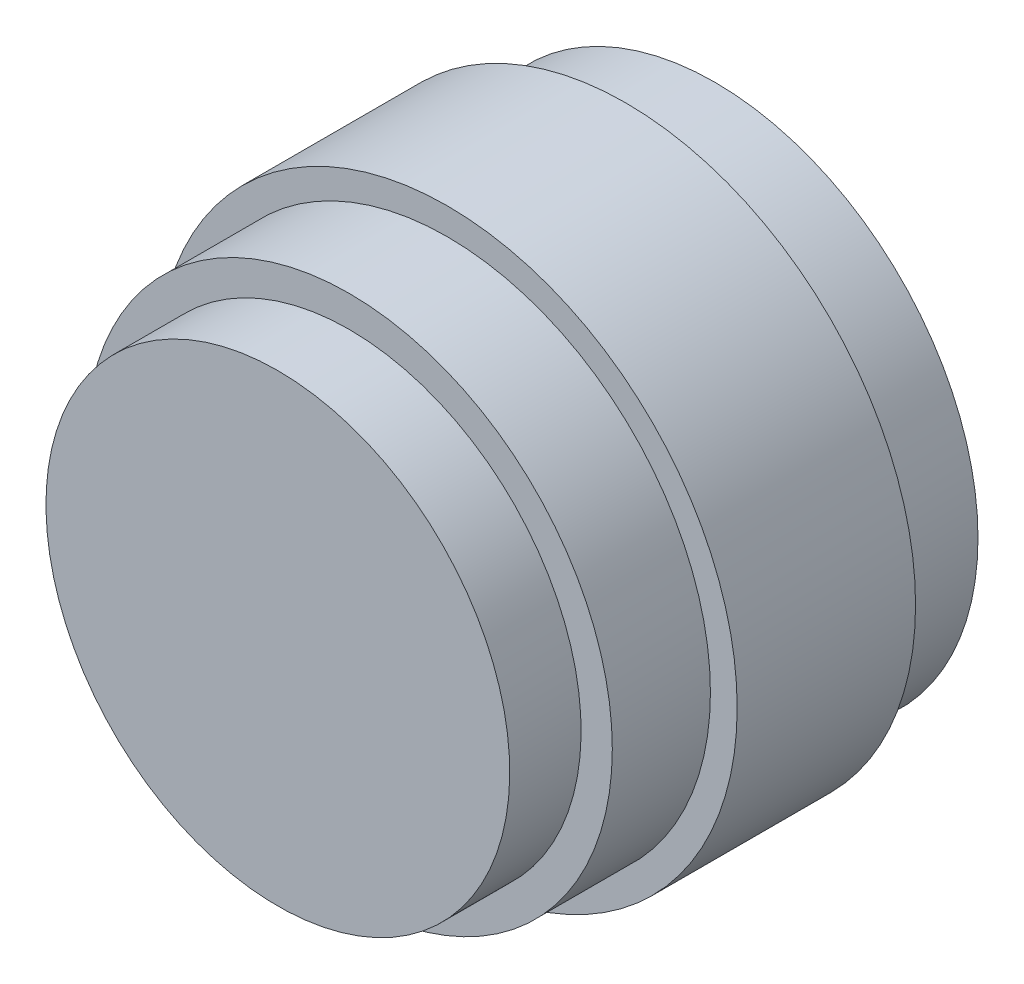
SolidWorks part; units mm, degrees
ref_plane "Front Plane" through (0, 0, 0) normal (0, 0, 1) x (1, 0, 0)
ref_plane "Top Plane" through (0, 0, 0) normal (0, 1, 0) x (1, 0, 0)
ref_plane "Right Plane" through (0, 0, 0) normal (1, 0, 0) x (0, 0, -1)
sketch "Sketch2" plane through (0, 0, 0) normal (1, 0, 0) x (0, 0, -1)
  line L0 (0, 29.5) -> (0, -29.5) construction
  line L1 (0, 33) -> (0, -33) construction
  line L2 (0, 29.5) -> (-10, 29.5)
  line L3 (-10, 29.5) -> (-10, 32.5)
  line L4 (-10, 32.5) -> (-30, 32.5)
  line L6 (-30, 29.5) -> (-41, 29.5)
  line L7 (-49, 26) -> (-49, -26) construction
  line L8 (0, 0) -> (-49, 0)
  line L9 (0, -38) -> (0, -48) construction
  line L10 (-41, 29.5) -> (-41, 26)
  line L11 (-41, 26) -> (-49, 26)
  line L12 (-41, -26) -> (-49, -26) construction
  line L13 (-41, -29.5) -> (-41, -26) construction
  line L14 (-30, -29.5) -> (-41, -29.5) construction
  line L16 (-10, -32.5) -> (-30, -32.5) construction
  line L17 (-10, -29.5) -> (-10, -32.5) construction
  line L18 (0, -29.5) -> (-10, -29.5) construction
  line L19 (-49, 0) -> (-49, 26)
  line L20 (0, 0) -> (0, 29.5)
  line L21 (-30, 29.5) -> (-30, 32.5)
  line L22 (-30, -32.5) -> (-30, -29.5) construction
  point P23 (-35.5, -29.5)
other "AlignGroup1" parameters "D1"=54.9325, "D2"=10, "D3"=30, "D4"=41, "D5"=49, "D6"=10, "D7"=20, "D8"=11, "D9"=8, "D10"=26
revolve "Revolve3" add sketch "Sketch2" angle 360 about L8
